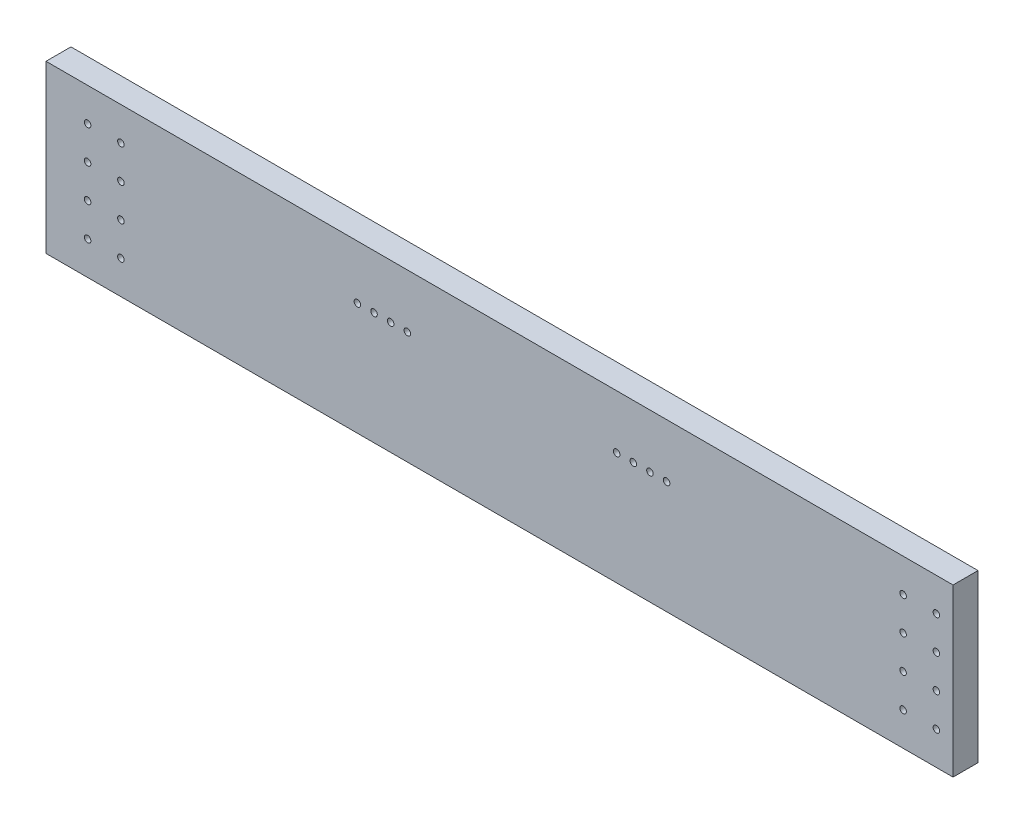
SolidWorks part; units mm, degrees
material "Pine"
ref_plane "Front Plane" through (0, 0, 0) normal (0, 0, 1) x (1, 0, 0)
ref_plane "Top Plane" through (0, 0, 0) normal (0, 1, 0) x (1, 0, 0)
ref_plane "Right Plane" through (0, 0, 0) normal (1, 0, 0) x (0, 0, -1)
sketch "Sketch1" plane through (0, 0, 0) normal (0, 1, 0) x (1, 0, 0)
  line L1 (0, 0) -> (660.4, 0) construction
  line L2 (0, 0) -> (0, 660.4) construction
  line L3 (0, 660.4) -> (660.4, 660.4) construction
  line L4 (660.4, 0) -> (660.4, 660.4) construction
  line L5 (-25.4, -25.4) -> (666.75, -25.4)
  line L6 (-25.4, -25.4) -> (-25.4, -6.35)
  line L7 (-25.4, -6.35) -> (666.75, -6.35)
  line L8 (666.75, -25.4) -> (666.75, -6.35)
  dimension "D1" = 660.4
  dimension "D2" = 19.05
  dimension "D3" = 6.35
  dimension "D4" = 25.4
  dimension "D5" = 6.35
extrude "Boss-Extrude1" add sketch "Sketch1" along normal mid plane 127
sketch "Sketch2" plane through (0, 0, 25.4) normal (0, 0, 1) x (1, 0, 0)
  line L0 (-25.4, 63.5) -> (-25.4, -63.5) construction
  line L1 (-6.35, -63.5) -> (-6.35, 63.5) construction
  line L2 (-25.4, -63.5) -> (666.75, -63.5) construction
  line L3 (-25.4, 63.5) -> (666.75, 63.5) construction
  circle A0 centre (6.35, -38.1) radius 2.4892
  circle A1 centre (31.75, -38.1) radius 2.4892
  dimension "D1" = 4.9784
  dimension "D3" = 12.7
  dimension "D5" = 25.4
  dimension "D2" = 25.4
  dimension "D4" = 19.05
extrude "Cut-Extrude1" cut sketch "Sketch2" against normal through all
pattern_linear "LPattern1" count 4 spacing 25.4 along (0, 1, 0) of "Cut-Extrude1"
sketch "Sketch3" plane through (0, 0, 25.4) normal (0, 0, 1) x (1, 0, 0)
  line L1 (0, -50.8) -> (660.4, -50.8) construction
  line L2 (0, -50.8) -> (0, 0) construction
  line L3 (0, 0) -> (660.4, 0) construction
  line L4 (660.4, -50.8) -> (660.4, 0) construction
  line L6 (-25.4, -63.5) -> (666.75, -63.5) construction
  line L7 (171.45, 0) -> (171.45, -50.8) construction
  line L8 (196.85, 25.654) -> (196.85, 3.429) construction
  line L9 (196.85, 3.429) -> (235.9913, 3.429) construction
  line L10 (196.85, 25.654) -> (199.517, 25.654) construction
  line L11 (199.517, 25.654) -> (199.517, 6.096) construction
  line L12 (199.517, 6.096) -> (235.9913, 6.096) construction
  line L13 (235.9913, 6.096) -> (235.9913, 3.429) construction
  line L14 (212.217, 22.479) -> (250.317, 22.479) construction
  line L15 (-25.4, 63.5) -> (-25.4, -63.5) construction
  line L16 (666.75, 63.5) -> (666.75, -63.5) construction
  line L17 (330.2, 0) -> (330.2, -50.8) construction
  circle A0 centre (212.217, 22.479) radius 2.4892
  circle A1 centre (224.917, 22.479) radius 2.4892
  circle A2 centre (237.617, 22.479) radius 2.4892
  circle A3 centre (250.317, 22.479) radius 2.4892
  dimension "D7" = 4.9784
  dimension "D8" = 12.7
  dimension "D9" = 12.7
  dimension "D10" = 12.7
  dimension "D12" = 12.7
  dimension "D1" = 50.8
  dimension "D2" = 12.7
  dimension "D3" = 171.45
  dimension "D4" = 3.429
  dimension "D5" = 2.667
  dimension "D6" = 22.225
  dimension "D11" = 19.05
  dimension "D13" = 25.4
  dimension "D14" = 6.35
  dimension "D15" = 25.4
extrude "Cut-Extrude2" cut sketch "Sketch3" against normal through all
ref_plane "Plane1" through (330.2, 0, 0) normal (1, 0, 0) x (0, 0, -1)
mirror "Mirror1" about plane through (330.2, 0, 0) normal (1, 0, 0) of "Cut-Extrude2", "LPattern1", "Cut-Extrude1"
